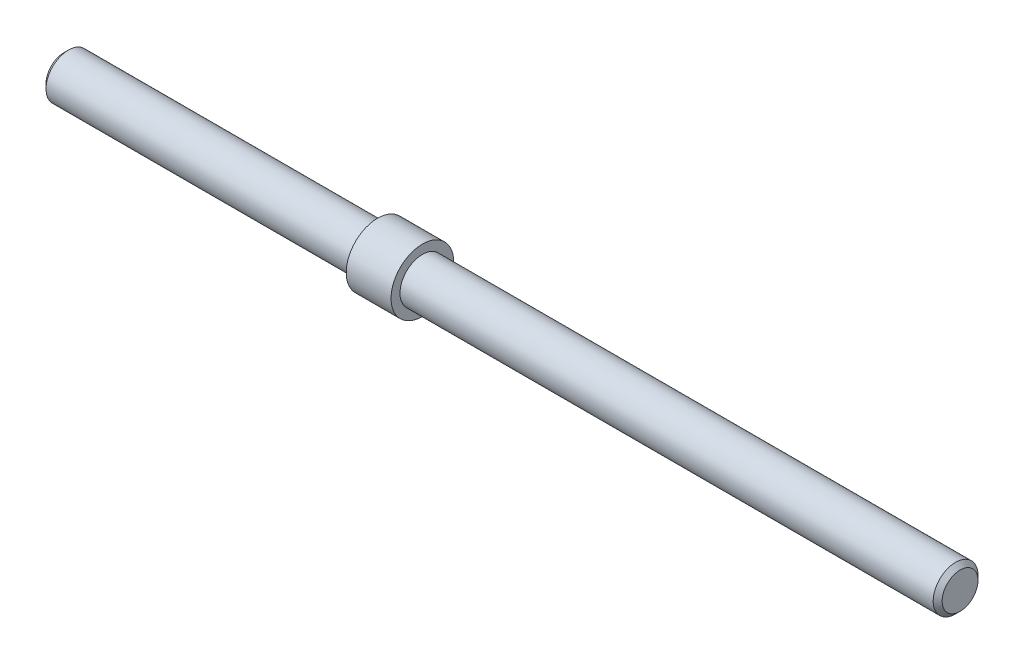
SolidWorks part; units mm, degrees
ref_plane "Front Plane" through (0, 0, 0) normal (0, 0, 1) x (1, 0, 0)
ref_plane "Top Plane" through (0, 0, 0) normal (0, 1, 0) x (1, 0, 0)
ref_plane "Right Plane" through (0, 0, 0) normal (1, 0, 0) x (0, 0, -1)
sketch "Sketch1" plane through (0, 0, 0) normal (1, 0, 0) x (0, 0, -1)
  circle A0 centre (0, 0) radius 5
  dimension "D1" = 10
extrude "Boss-Extrude1" add sketch "Sketch1" along normal blind 200
chamfer "Chamfer1" distance 1 angle 45 2 edges at (200, 0, -5) (0, 0, -5)
sketch "Sketch2" plane through (0, 0, 0) normal (1, 0, 0) x (0, 0, -1)
  circle A0 centre (0, 0) radius 7
extrude "Boss-Extrude2" add sketch "Sketch2" along normal blind 10 from offset 70
